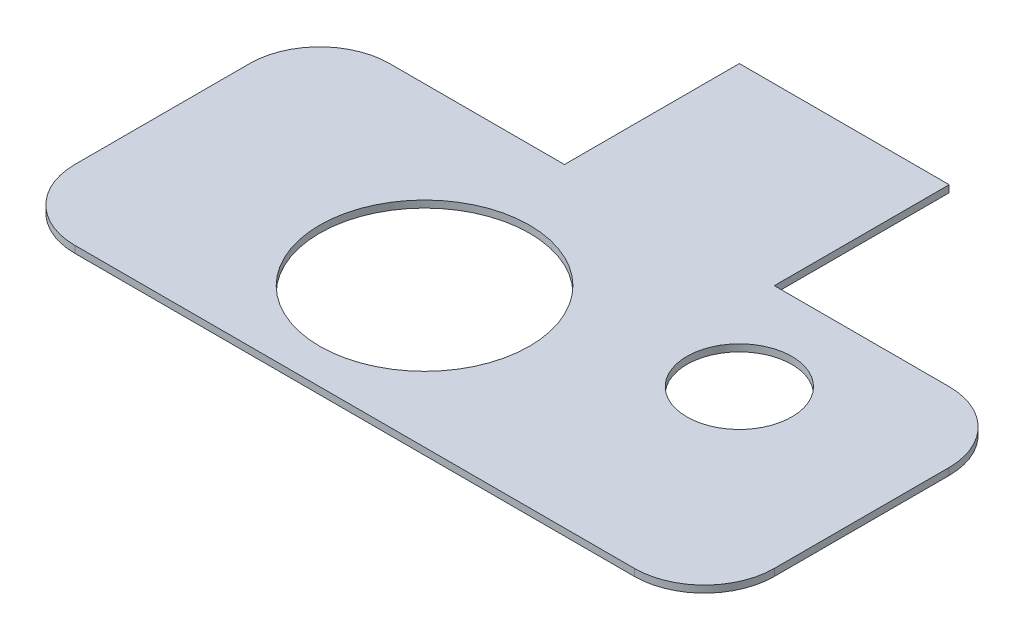
SolidWorks part; units mm, degrees
ref_plane "Front Plane" through (0, 0, 0) normal (0, 0, 1) x (1, 0, 0)
ref_plane "Top Plane" through (0, 0, 0) normal (0, 1, 0) x (1, 0, 0)
ref_plane "Right Plane" through (0, 0, 0) normal (1, 0, 0) x (0, 0, -1)
sketch "Sketch1" plane through (0, 0, 0) normal (0, 1, 0) x (1, 0, 0)
  line L0 (65, 45) -> (90, 45)
  line L1 (10, 0) -> (90, 0)
  line L2 (0, 10) -> (0, 35)
  line L3 (10, 45) -> (35, 45)
  line L4 (100, 10) -> (100, 35)
  line L6 (35, 45) -> (35, 70)
  line L7 (35, 70) -> (65, 70)
  line L8 (65, 45) -> (65, 70)
  circle A0 centre (40, 20) radius 15
  circle A1 centre (75, 30) radius 7.5
  arc A2 (90, 45) -> (100, 35) centre (90, 35) cw
  arc A3 (90, 0) -> (100, 10) centre (90, 10) ccw
  arc A4 (10, 0) -> (0, 10) centre (10, 10) cw
  arc A5 (0, 35) -> (10, 45) centre (10, 35) cw
  point P17 (100, 0)
  point P20 (0, 0)
  point P23 (0, 45)
  dimension "D9" = 30
  dimension "D10" = 15
  dimension "D12" = 10
  dimension "D1" = 100
  dimension "D2" = 45
  dimension "D3" = 35
  dimension "D4" = 30
  dimension "D5" = 25
  dimension "D6" = 40
  dimension "D7" = 30
  dimension "D8" = 20
  dimension "D11" = 75
extrude "Boss-Extrude1" add sketch "Sketch1" along normal blind 1 contours L4 A2 L0 L8 L7 L6 L3 A5 L2 A4 L1 A3
